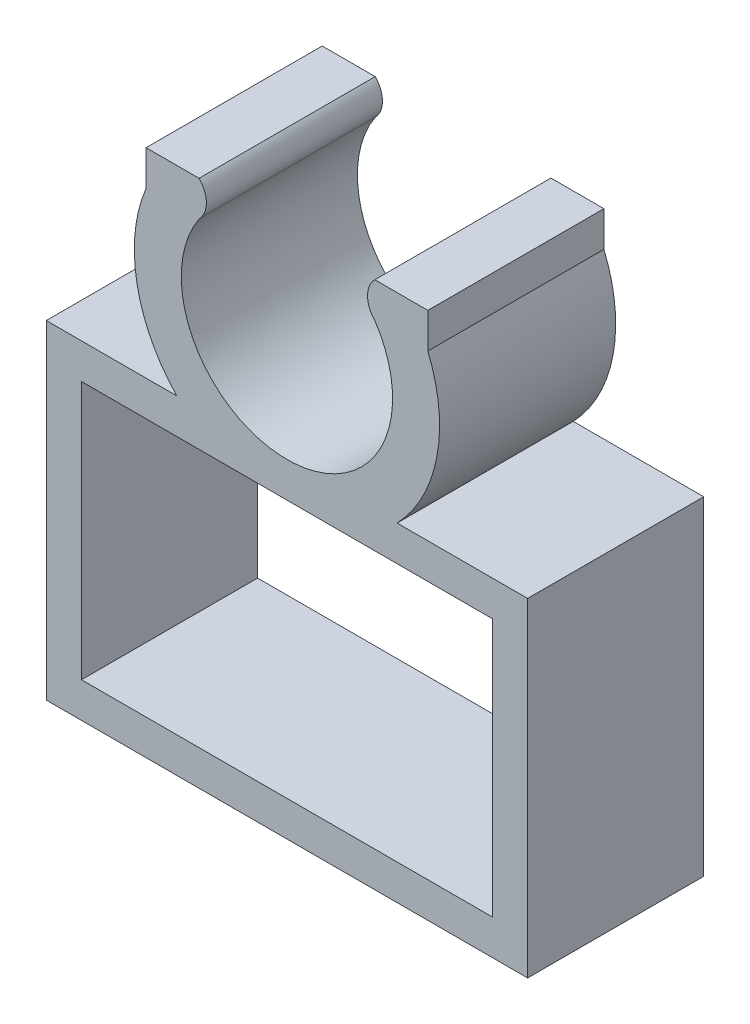
SolidWorks part; units mm, degrees
ref_plane "Alzado" through (0, 0, 0) normal (0, 0, 1) x (1, 0, 0)
ref_plane "Planta" through (0, 0, 0) normal (0, 1, 0) x (1, 0, 0)
ref_plane "Vista lateral" through (0, 0, 0) normal (1, 0, 0) x (0, 0, -1)
sketch "Croquis1" plane through (0, 0, 0) normal (0, 0, 1) x (1, 0, 0)
  line L0 (-48.9571, 5.2183) -> (-48.9571, 19.2183) construction
  line L1 (-66.4571, 5.2183) -> (-31.4571, 5.2183)
  line L2 (-66.4571, 5.2183) -> (-66.4571, -16.7817)
  line L3 (-66.4571, -16.7817) -> (-31.4571, -16.7817)
  line L4 (-31.4571, 5.2183) -> (-31.4571, -16.7817)
  line L6 (-69.4571, 8.2183) -> (-69.4571, -19.7817)
  line L7 (-69.4571, -19.7817) -> (-28.4571, -19.7817)
  line L8 (-28.4571, 8.2183) -> (-28.4571, -19.7817)
  line L9 (-69.4571, 8.2183) -> (-58.3379, 8.2183)
  line L10 (-28.4571, 8.2183) -> (-39.5763, 8.2183)
  line L11 (-48.9571, 8.2183) -> (-48.9571, 22.2183) construction
  line L12 (-48.9571, 22.2183) -> (-60.9571, 22.2183) construction
  line L13 (-48.9571, 22.2183) -> (-36.9571, 22.2183) construction
  line L14 (-56.4404, 22.2183) -> (-56.4404, 24.2183) construction
  line L15 (-41.4738, 22.2183) -> (-41.4738, 24.2183) construction
  line L16 (-56.4404, 22.2183) -> (-56.4404, 25.2183) construction
  line L17 (-56.4404, 25.2183) -> (-60.9571, 25.2183)
  line L18 (-60.9571, 25.2183) -> (-60.9571, 22.2183)
  line L19 (-41.4738, 25.2183) -> (-36.9571, 25.2183)
  line L20 (-36.9571, 25.2183) -> (-36.9571, 22.2183)
  arc A2 (-60.9571, 22.2183) -> (-58.3379, 8.2183) centre (-48.9571, 17.2183) ccw
  arc A3 (-56.4404, 22.2183) -> (-41.4738, 22.2183) centre (-48.9571, 17.2183) ccw
  arc A4 (-36.9571, 22.2183) -> (-39.5763, 8.2183) centre (-48.9571, 17.2183) cw
  arc A5 (-56.4404, 22.2183) -> (-56.4404, 25.2183) centre (-57.9404, 23.7183) ccw
  arc A6 (-41.4738, 22.2183) -> (-41.4738, 25.2183) centre (-39.9738, 23.7183) cw
  dimension "D9" = 9
  dimension "D10" = 13
  dimension "D12" = 13
  dimension "D13" = 2.1213
  dimension "D14" = 2.1213
  dimension "D1" = 35
  dimension "D2" = 22
  dimension "D3" = 3
  dimension "D4" = 3
  dimension "D5" = 3
  dimension "D6" = 28
  dimension "D8" = 14
  dimension "D11" = 14
  dimension "D15" = 4.5167
  dimension "D16" = 3
  dimension "D17" = 3
  dimension "D18" = 4.5167
extrude "Saliente-Extruir1" add sketch "Croquis1" along normal blind 15
